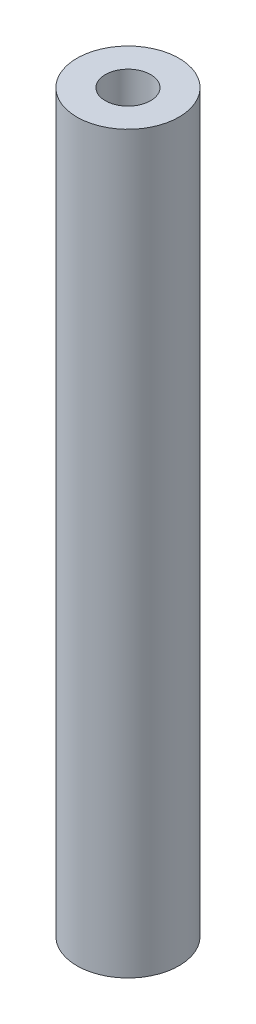
SolidWorks part; units mm, degrees
ref_plane "Front Plane" through (0, 0, 0) normal (0, 0, 1) x (1, 0, 0)
ref_plane "Top Plane" through (0, 0, 0) normal (0, 1, 0) x (1, 0, 0)
ref_plane "Right Plane" through (0, 0, 0) normal (1, 0, 0) x (0, 0, -1)
sketch "Sketch1" plane through (0, 0, 0) normal (0, 1, 0) x (1, 0, 0)
  circle A0 centre (0, 0) radius 1.2
  circle A1 centre (0, 0) radius 2.7
  dimension "D1" = 2.4
  dimension "D2" = 1.5
extrude "Boss-Extrude1" add sketch "Sketch1" along normal blind 38.9
